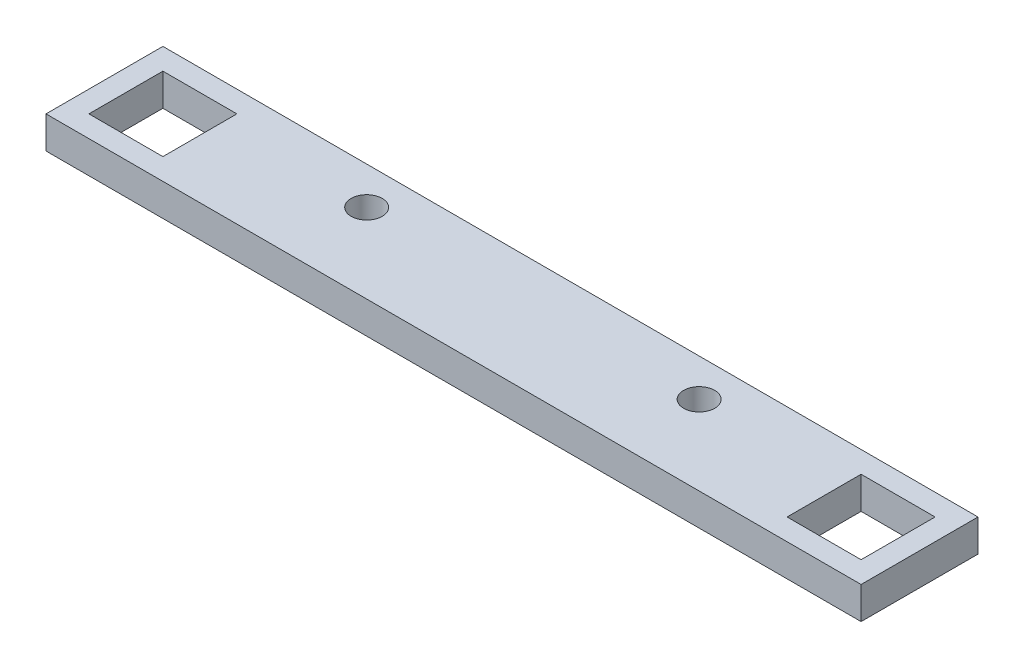
SolidWorks part; units mm, degrees
material "Chêne"
ref_plane "Plan de face" through (0, 0, 0) normal (0, 0, 1) x (1, 0, 0)
ref_plane "Plan de dessus" through (0, 0, 0) normal (0, 1, 0) x (1, 0, 0)
ref_plane "Plan de droite" through (0, 0, 0) normal (1, 0, 0) x (0, 0, -1)
sketch "Esquisse1" plane through (0, 0, 0) normal (0, 1, 0) x (1, 0, 0)
  line L0 (22.5, 7.4) -> (53.5, 7.4) construction
  line L1 (0, 0) -> (76, 0)
  line L2 (0, 0) -> (0, 10.9)
  line L3 (0, 10.9) -> (76, 10.9)
  line L4 (76, 0) -> (76, 10.9)
  line L5 (2, 2) -> (8.9, 2)
  line L6 (2, 2) -> (2, 8.9)
  line L7 (2, 8.9) -> (8.9, 8.9)
  line L8 (8.9, 2) -> (8.9, 8.9)
  line L9 (74, 2) -> (67.1, 2)
  line L10 (74, 2) -> (74, 8.9)
  line L11 (74, 8.9) -> (67.1, 8.9)
  line L12 (67.1, 2) -> (67.1, 8.9)
  circle A0 centre (22.5, 7.4) radius 1.45
  circle A1 centre (53.5, 7.4) radius 1.45
  point P17 (38, 10.9)
  point P18 (38, 7.4)
  dimension "D2" = 2.9
  dimension "D3" = 2.9
  dimension "D1" = 6.9
  dimension "D4" = 2
  dimension "D5" = 2
  dimension "D6" = 2
  dimension "D7" = 2
  dimension "D8" = 31
  dimension "D9" = 76
  dimension "D10" = 3.5
extrude "Boss.-Extru.1" add sketch "Esquisse1" along normal blind 3
